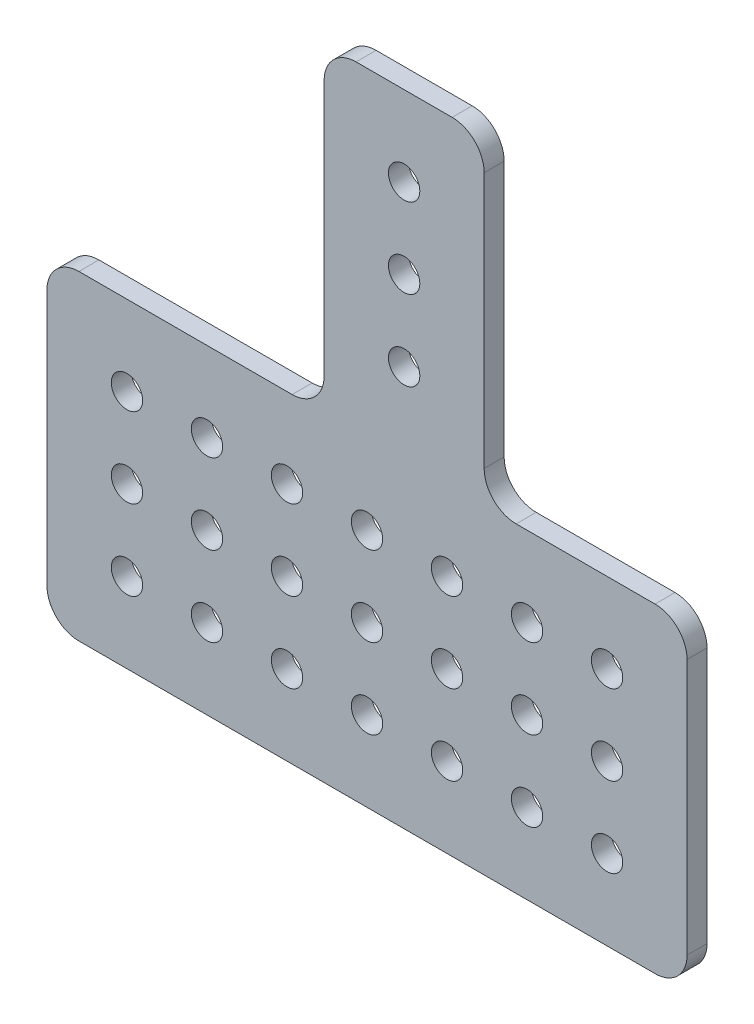
SolidWorks part; units mm, degrees
ref_plane "Front Plane" through (0, 0, 0) normal (0, 0, 1) x (1, 0, 0)
ref_plane "Top Plane" through (0, 0, 0) normal (0, 1, 0) x (1, 0, 0)
ref_plane "Right Plane" through (0, 0, 0) normal (1, 0, 0) x (0, 0, -1)
sketch "Sketch1" plane through (0, 0, 0) normal (0, 0, 1) x (1, 0, 0)
  line L1 (0, 0) -> (101.6, 0)
  line L2 (0, 0) -> (0, -50.8)
  line L3 (0, -50.8) -> (101.6, -50.8)
  line L4 (101.6, 0) -> (101.6, -50.8)
  line L5 (43.9928, 0) -> (69.3928, 0)
  line L6 (43.9928, 0) -> (43.9928, 50.8)
  line L7 (43.9928, 50.8) -> (69.3928, 50.8)
  line L8 (69.3928, 0) -> (69.3928, 50.8)
  circle A0 centre (56.6928, 12.7) radius 2.4892
  circle A1 centre (12.7, -38.1) radius 2.4892
  circle A2 centre (25.4, -38.1) radius 2.4892
  circle A3 centre (38.1, -38.1) radius 2.4892
  circle A4 centre (50.8, -38.1) radius 2.4892
  circle A5 centre (63.5, -38.1) radius 2.4892
  circle A6 centre (76.2, -38.1) radius 2.4892
  circle A7 centre (88.9, -38.1) radius 2.4892
  circle A8 centre (25.4, -25.4) radius 2.4892
  circle A9 centre (38.1, -25.4) radius 2.4892
  circle A10 centre (50.8, -25.4) radius 2.4892
  circle A11 centre (63.5, -25.4) radius 2.4892
  circle A12 centre (76.2, -25.4) radius 2.4892
  circle A13 centre (88.9, -25.4) radius 2.4892
  circle A14 centre (25.4, -12.7) radius 2.4892
  circle A15 centre (38.1, -12.7) radius 2.4892
  circle A16 centre (50.8, -12.7) radius 2.4892
  circle A17 centre (63.5, -12.7) radius 2.4892
  circle A18 centre (76.2, -12.7) radius 2.4892
  circle A19 centre (88.9, -12.7) radius 2.4892
  circle A20 centre (12.7, -25.4) radius 2.4892
  circle A21 centre (12.7, -12.7) radius 2.4892
  circle A22 centre (56.6928, 25.4) radius 2.4892
  circle A23 centre (56.6928, 38.1) radius 2.4892
  point P13 (0, 0)
  dimension "D5" = 12.7
  dimension "D6" = 43.9928
  dimension "D12" = 4.9784
  dimension "D1" = 25.4
  dimension "D2" = 50.8
  dimension "D3" = 101.6
  dimension "D4" = 12.7
  dimension "D7" = 12.7
  dimension "D8" = 12.7
  dimension "D13" = 12.7
  dimension "D14" = 12.7
  dimension "D15" = 12.7
  dimension "D16" = 12.7
  dimension "D9" = 7
  dimension "D10" = 3
  dimension "D11" = 3
extrude "Boss-Extrude1" add sketch "Sketch1" along normal mid plane 3.175 contours L4 L1 L2 L3 A21 A20 A19 A18 A17 A16 A15 A14 A13 A12 A11 A10 A9 A8 A7 A6 A5 A4 A3 A2 A1 | L1 L8 L7 L6 A23 A22 A0
fillet "Fillet1" radius 5.08 8 edges at (101.6, -50.8, 0) (0, -50.8, 0) (0, 0, 0) (43.9928, 0, 0) (69.3928, 50.8, 0) (69.3928, 0, 0) (101.6, 0, 0) (43.9928, 50.8, 0)
